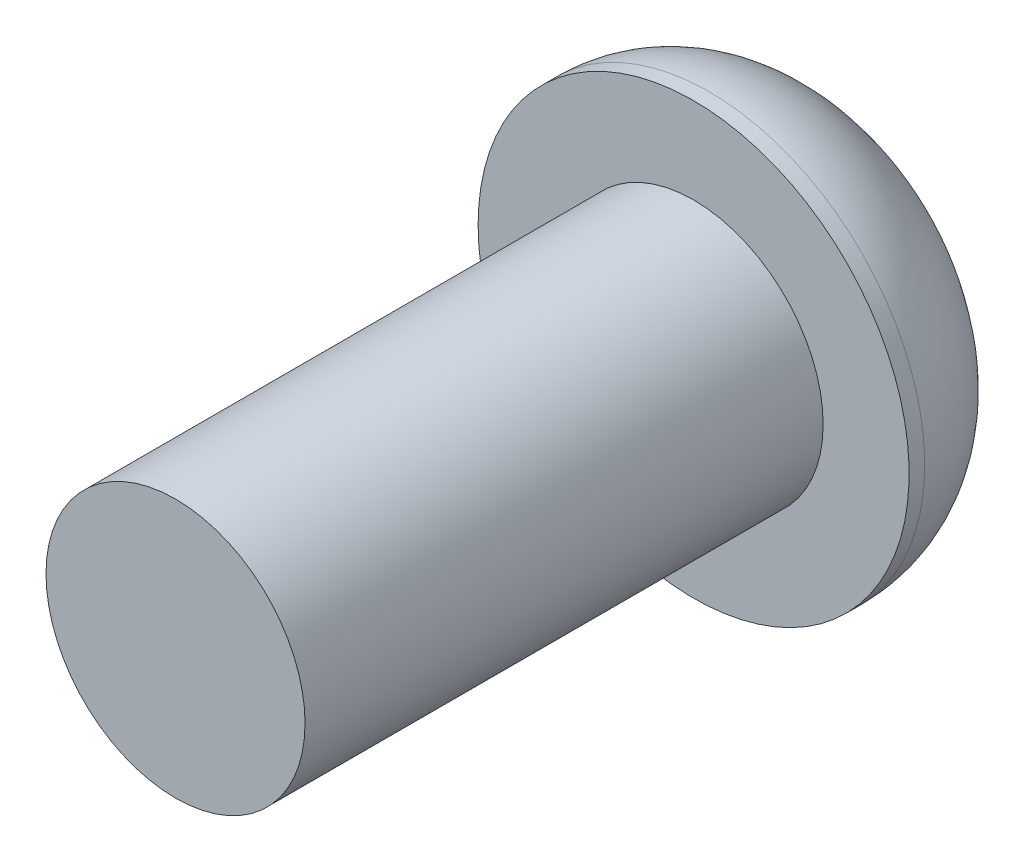
SolidWorks part; units mm, degrees
ref_plane "Front Plane" through (0, 0, 0) normal (0, 0, 1) x (1, 0, 0)
ref_plane "Top Plane" through (0, 0, 0) normal (0, 1, 0) x (1, 0, 0)
ref_plane "Right Plane" through (0, 0, 0) normal (1, 0, 0) x (0, 0, -1)
sketch "Sketch1" plane through (0, 0, 0) normal (0, 0, 1) x (1, 0, 0)
  circle A0 centre (0, 0) radius 2.5
  dimension "D1" = 5
extrude "Boss-Extrude1" add sketch "Sketch1" along normal blind 10
sketch "Sketch2" plane through (0, 0, 0) normal (0, 0, -1) x (-1, 0, 0)
  circle A0 centre (0, 0) radius 4.1596
extrude "Boss-Extrude2" add sketch "Sketch2" along normal blind 2.8
fillet "Fillet1" radius 2.5 1 edges at (-4.1596, 0, -2.8)
sketch "Sketch3" plane through (0, 0, -2.8) normal (0, 0, -1) x (-1, 0, 0)
  line L1 (1.3924, -0.6365) -> (1.2475, 0.8876)
  line L2 (1.2475, 0.8876) -> (-0.145, 1.5241)
  line L3 (-0.145, 1.5241) -> (-1.3924, 0.6365)
  line L4 (-1.3924, 0.6365) -> (-1.2475, -0.8876)
  line L5 (-1.2475, -0.8876) -> (0.145, -1.5241)
  line L6 (0.145, -1.5241) -> (1.3924, -0.6365)
  circle A0 centre (0, 0) radius 1.3259 construction
extrude "Cut-Extrude1" cut sketch "Sketch3" against normal blind 2
